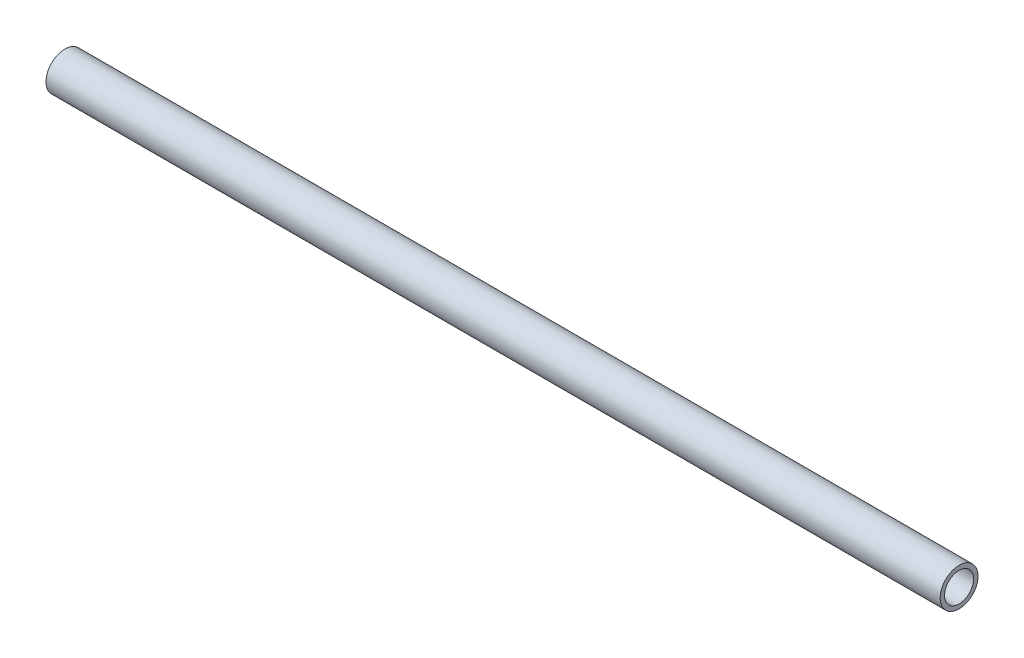
SolidWorks part; units mm, degrees
material "AISI 4130 Steel, annealed at 865C"
ref_plane "X-Y Datum" through (0, 0, 0) normal (0, 0, 1) x (1, 0, 0)
ref_plane "X-Z Datum" through (0, 0, 0) normal (0, 1, 0) x (1, 0, 0)
ref_plane "Y-Z Datum" through (0, 0, 0) normal (1, 0, 0) x (0, 0, -1)
sketch "Sketch1" plane through (0, 0, 0) normal (1, 0, 0) x (0, 0, -1)
  circle A0 centre (0, 0) radius 6.35
  circle A1 centre (0, 0) radius 4.8768
  dimension "D1" = 12.7
  dimension "D2" = 9.7536
extrude "Boss-Extrude1" add sketch "Sketch1" along normal up to surface (149.9062 mm away) and the other way up to surface (149.9062 mm away)
